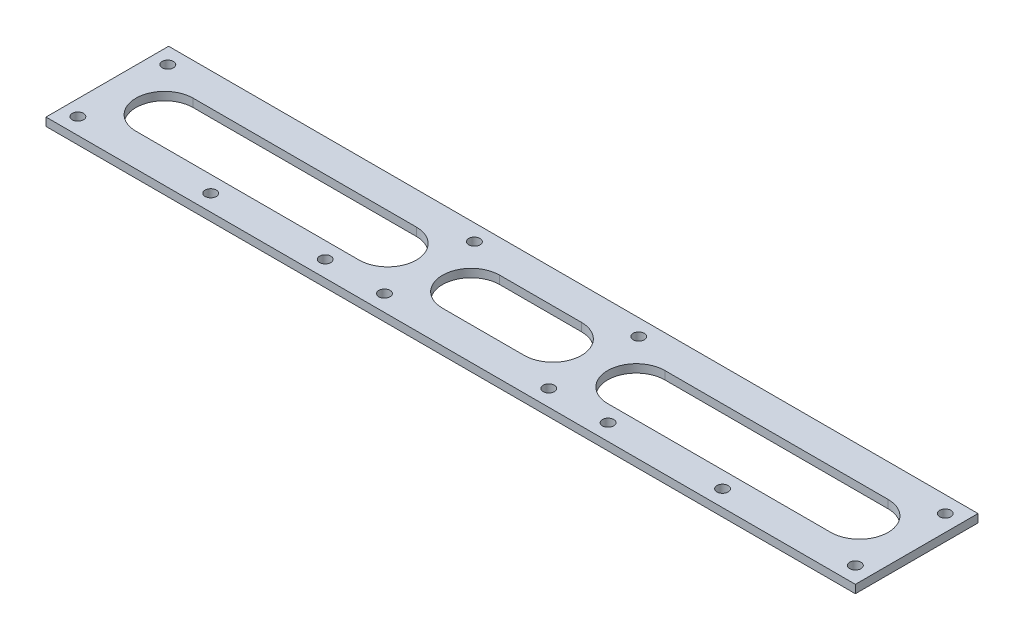
SolidWorks part; units mm, degrees
material "Thornel Mat VMA"
ref_plane "前视基准面" through (0, 0, 0) normal (0, 0, 1) x (1, 0, 0)
ref_plane "上视基准面" through (0, 0, 0) normal (0, 1, 0) x (1, 0, 0)
ref_plane "右视基准面" through (0, 0, 0) normal (1, 0, 0) x (0, 0, -1)
sketch "草图1" plane through (0, 0, 0) normal (0, 1, 0) x (1, 0, 0)
  line L1 (99, 15) -> (-99, 15)
  line L2 (99, 15) -> (99, -15)
  line L3 (99, -15) -> (-99, -15)
  line L4 (-99, 15) -> (-99, -15)
  line L5 (99, 15) -> (-99, -15) construction
  line L6 (99, -15) -> (-99, 15) construction
  point P0 (0, 0)
  dimension "D1" = 198
  dimension "D2" = 30
extrude "凸台-拉伸1" add sketch "草图1" along normal blind 2
hole_wizard "孔1" positions "草图2" profile "草图3" legacy
sketch "草图2" plane through (0, 2, 0) normal (0, 1, 0) x (1, 0, 0)
  point P0 (95, 11)
  point P3 (95, -11)
  point P6 (20, 11)
  point P9 (20, -11)
  point P12 (-95.2, 11)
  point P15 (-95.2, -11)
  point P18 (-20.2, 11)
  point P21 (-20.2, -11)
  point P24 (-34.7, -11)
  point P27 (-62.7, -11)
  point P30 (62.5, -11)
  point P33 (34.5, -11)
sketch "草图3" plane through (95, 2, -11) normal (1, 0, 0) x (0, 0, 1)
  line L0 (0, 0) -> (0, 100)
  line L1 (0, 100) -> (1.375, 100)
  line L2 (1.375, 100) -> (1.375, 0)
  line L3 (1.375, 0) -> (0, 0)
  line L4 (0, 110) -> (0, -10) construction
  dimension "直径" = 2.75
  dimension "深度" = 100
sketch "草图4" plane through (0, 2, 0) normal (0, 1, 0) x (1, 0, 0)
  line L0 (-10, 0) -> (10, 0) construction
  line L1 (-10, 7) -> (10, 7)
  line L2 (-10, -7) -> (10, -7)
  line L3 (-20.2, 11) -> (-20.2, -11) construction
  line L4 (0, 15) -> (0, -15) construction
  line L5 (99, 15) -> (-99, 15) construction
  line L6 (-99, -15) -> (99, -15) construction
  line L7 (-95.2, 11) -> (-95.2, -11) construction
  line L8 (-95.2, 0) -> (-20.2, 0) construction
  line L9 (-85, 0) -> (-30.4, 0) construction
  line L10 (-85, 7) -> (-30.4, 7)
  line L11 (-85, -7) -> (-30.4, -7)
  line L12 (-23.4, 0) -> (-17, 0) construction
  line L13 (85, 0) -> (30.4, 0) construction
  line L14 (85, 7) -> (30.4, 7)
  line L15 (85, -7) -> (30.4, -7)
  arc A0 (-10, 7) -> (-10, -7) centre (-10, 0) ccw
  arc A1 (10, -7) -> (10, 7) centre (10, 0) ccw
  arc A2 (-85, 7) -> (-85, -7) centre (-85, 0) ccw
  arc A3 (-30.4, -7) -> (-30.4, 7) centre (-30.4, 0) ccw
  arc A4 (85, 7) -> (85, -7) centre (85, 0) cw
  arc A5 (30.4, -7) -> (30.4, 7) centre (30.4, 0) cw
  point P3 (0, 0)
  point P24 (-57.7, 0)
  point P25 (-57.7, 0)
  point P32 (-20.2, 0)
  point P35 (-20.2, 0)
  point P38 (57.7, 0)
  dimension "D1" = 7
  dimension "D2" = 20
extrude "切除-拉伸1" cut sketch "草图4" against normal through all both and the other way through all
